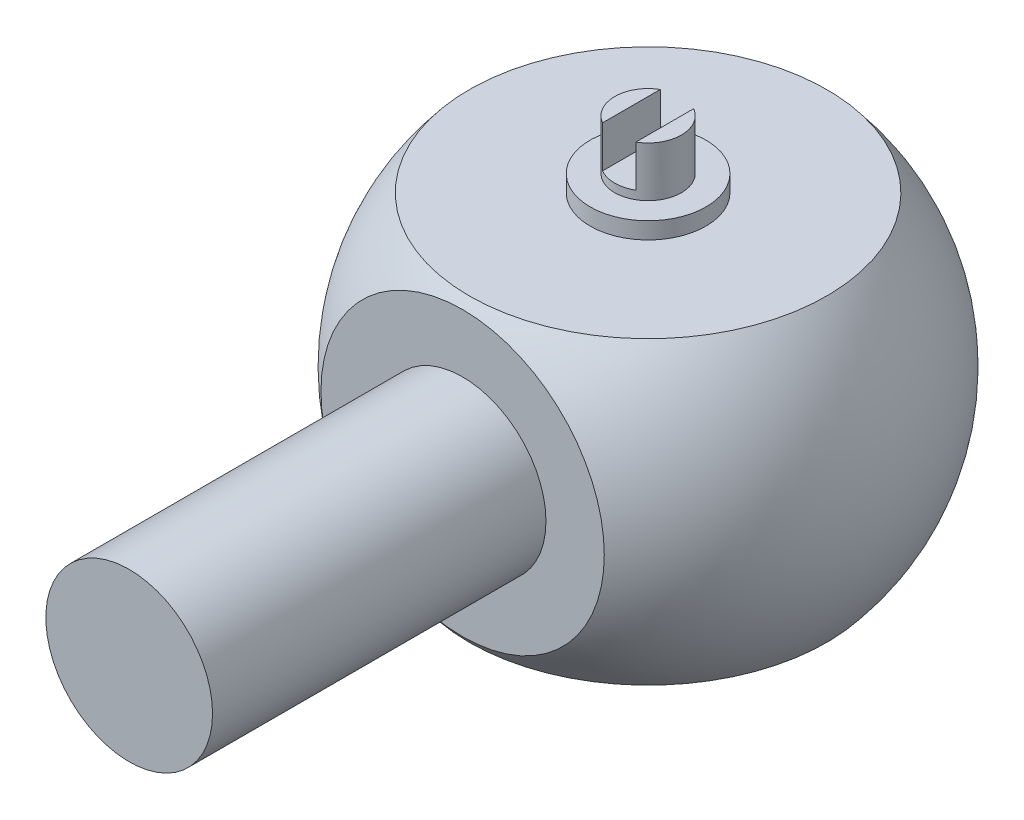
SolidWorks part; units mm, degrees
material "ABS"
ref_plane "Alzado" through (0, 0, 0) normal (0, 0, 1) x (1, 0, 0)
ref_plane "Planta" through (0, 0, 0) normal (0, 1, 0) x (1, 0, 0)
ref_plane "Vista lateral" through (0, 0, 0) normal (1, 0, 0) x (0, 0, -1)
sketch "Croquis1" plane through (0, 0, 0) normal (0, 0, 1) x (1, 0, 0)
  line L1 (0, 9) -> (0, -11)
  line L3 (0, 9) -> (0, 10)
  line L4 (3.4729, 9) -> (10.7238, 9)
  line L5 (2, 10) -> (3.4729, 10)
  line L6 (3.4729, 9) -> (3.4729, 10)
  line L8 (3.4552, -9) -> (10.7238, -9)
  line L9 (0, -11) -> (0, -12)
  line L10 (2, -10) -> (3.4552, -10)
  line L11 (3.4552, -9) -> (3.4552, -10)
  line L13 (0, 10) -> (0, 13)
  line L14 (0, 13) -> (2, 13)
  line L15 (2, 10) -> (2, 13)
  line L17 (0, -12) -> (0, -15)
  line L18 (0, -15) -> (2, -15)
  line L19 (2, -10) -> (2, -15)
  arc A2 (10.7238, -9) -> (10.7238, 9) centre (0, 0) ccw
  dimension "D1" = 20
  dimension "D2" = 9
  dimension "D3" = 1
  dimension "D4" = 1
  dimension "D5" = 1
  dimension "D6" = 3
  dimension "D13" = 14
  dimension "D7" = 3
  dimension "D8" = 1
  dimension "D10" = 18
revolve "Revolución2" add sketch "Croquis1" angle 360 about L1
sketch "Croquis2" plane through (0, 0, 0) normal (1, 0, 0) x (0, 0, -1)
  line L0 (0, 0) -> (-15, 0) construction
  line L2 (-18.8741, -8.4979) -> (-11.1259, -8.4979)
  line L3 (-18.8741, -8.4979) -> (-18.8741, 8.4979)
  line L4 (-18.8741, 8.4979) -> (-11.1259, 8.4979)
  line L5 (-11.1259, -8.4979) -> (-11.1259, 8.4979)
  line L6 (-18.8741, -8.4979) -> (-11.1259, 8.4979) construction
  line L7 (-18.8741, 8.4979) -> (-11.1259, -8.4979) construction
  circle A0 centre (0, 0) radius 14 construction
  dimension "D1" = 15
extrude "Cortar-Extruir1" cut sketch "Croquis2" against normal blind 10 and the other way blind 15
sketch "Croquis3" plane through (0, 0, 0) normal (0, 1, 0) x (1, 0, 0)
  circle A0 centre (0, 0) radius 1.5
  dimension "D1" = 3
sketch "Croquis4" plane through (0, 0, 11.1259) normal (0, 0, 1) x (1, 0, 0)
  circle A0 centre (0, 0) radius 5
  dimension "D1" = 10
extrude "Saliente-Extruir2" add sketch "Croquis4" along normal blind 20
sketch "Croquis5" plane through (0, 0, 0) normal (1, 0, 0) x (0, 0, -1)
  line L0 (0, 0) -> (-38.8591, 0)
sketch "Croquis6" plane through (0, 0, 0) normal (0, 0, 1) x (1, 0, 0)
  line L0 (2, 13) -> (-2, 13) construction
  line L1 (-1, 13) -> (1, 13)
  line L2 (-1, 13) -> (-1, 10.5)
  line L3 (-1, 10.5) -> (1, 10.5)
  line L4 (1, 13) -> (1, 10.5)
  line L6 (-2, 13) -> (-2, 10) construction
  dimension "D1" = 2.5
  dimension "D2" = 2
  dimension "D3" = 1
extrude "Cortar-Extruir2" cut sketch "Croquis6" against normal blind 2 and the other way blind 2
